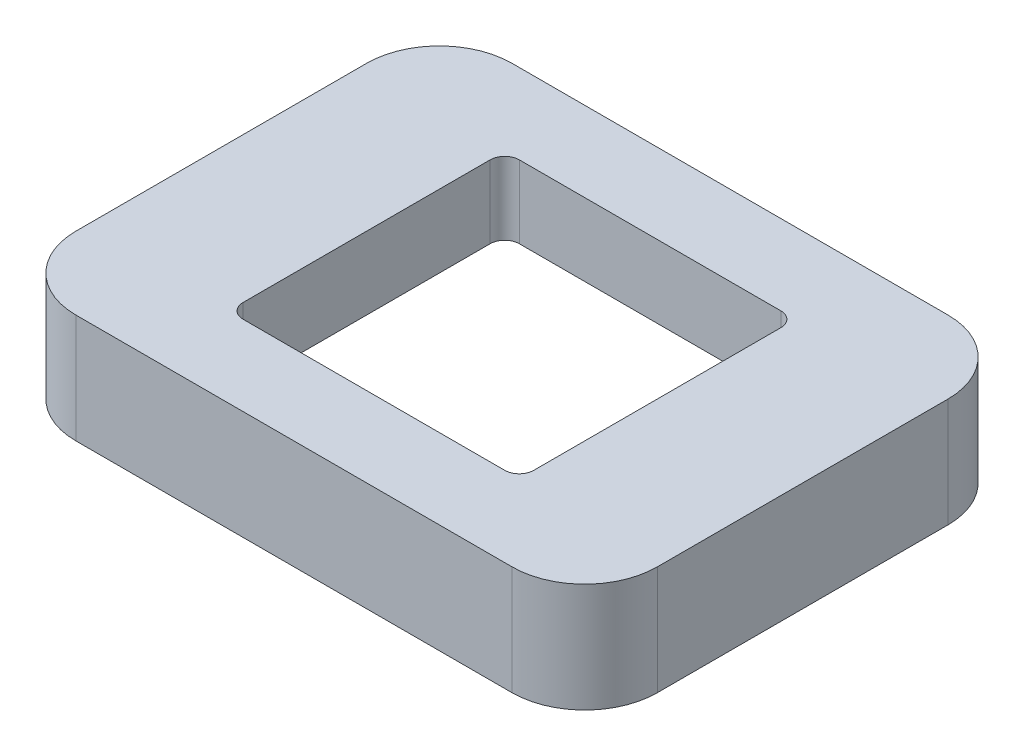
SolidWorks part; units mm, degrees
ref_plane "Plan de face" through (0, 0, 0) normal (0, 0, 1) x (1, 0, 0)
ref_plane "Plan de dessus" through (0, 0, 0) normal (0, 1, 0) x (1, 0, 0)
ref_plane "Plan de droite" through (0, 0, 0) normal (1, 0, 0) x (0, 0, -1)
sketch "Esquisse1" plane through (0, 0, 0) normal (0, 1, 0) x (1, 0, 0)
  line L1 (10, 0) -> (70, 0)
  line L2 (0, -10) -> (0, -50)
  line L3 (10, -60) -> (70, -60)
  line L4 (80, -10) -> (80, -50)
  line L13 (58, -49) -> (22, -49)
  line L14 (60, -47) -> (60, -13)
  line L15 (58, -11) -> (22, -11)
  line L16 (20, -47) -> (20, -13)
  line L17 (60, -49) -> (20, -11) construction
  line L18 (60, -11) -> (20, -49) construction
  arc A0 (0, -50) -> (10, -60) centre (10, -50) ccw
  arc A1 (80, -50) -> (70, -60) centre (70, -50) cw
  arc A2 (0, -10) -> (10, 0) centre (10, -10) cw
  arc A3 (70, 0) -> (80, -10) centre (70, -10) cw
  arc A12 (60, -13) -> (58, -11) centre (58, -13) ccw
  arc A13 (22, -11) -> (20, -13) centre (22, -13) ccw
  arc A14 (20, -47) -> (22, -49) centre (22, -47) ccw
  arc A15 (60, -47) -> (58, -49) centre (58, -47) cw
  point P9 (80, -60)
  point P12 (0, 0)
  point P15 (80, 0)
  point P16 (40, -30)
  dimension "D3" = 10
  dimension "D4" = 40
  dimension "D6" = 38
  dimension "D7" = 30
  dimension "D8" = 2
  dimension "D1" = 80
  dimension "D2" = 60
  dimension "D5" = 40
extrude "Boss.-Extru.1" add sketch "Esquisse1" along normal blind 15
sketch "Esquisse2" plane through (0, 0, 0) normal (0, -1, 0) x (1, 0, 0)
  line L0 (70, 0) -> (10, 0) construction
  line L1 (8, 57) -> (72, 57)
  line L2 (3, 52) -> (3, 8)
  line L3 (8, 3) -> (72, 3)
  line L4 (77, 52) -> (77, 8)
  line L5 (10, 60) -> (70, 60) construction
  line L6 (80, 50) -> (80, 10) construction
  line L7 (0, 10) -> (0, 50) construction
  arc A0 (3, 52) -> (8, 57) centre (8, 52) cw
  arc A1 (3, 8) -> (8, 3) centre (8, 8) ccw
  arc A2 (72, 3) -> (77, 8) centre (72, 8) ccw
  arc A3 (77, 52) -> (72, 57) centre (72, 52) ccw
  dimension "D5" = 5
  dimension "D1" = 3
  dimension "D2" = 3
  dimension "D3" = 3
  dimension "D4" = 3
extrude "Enlèv. mat.-Extru.1" cut sketch "Esquisse2" against normal blind 5
sketch "Esquisse3" plane through (0, 5, 0) normal (0, -1, 0) x (1, 0, 0)
  line L0 (65, 13.5) -> (65, 46.5) construction
  line L1 (65, 13.5) -> (15, 13.5) construction
  line L2 (15, 13.5) -> (15, 46.5) construction
  line L3 (15, 46.5) -> (65, 46.5) construction
  line L6 (72, 57) -> (8, 57) construction
  line L7 (3, 52) -> (3, 8) construction
  circle A0 centre (65, 13.5) radius 2.8
  circle A2 centre (65, 46.5) radius 2.8
  circle A3 centre (15, 13.5) radius 2.8
  circle A4 centre (15, 46.5) radius 2.8
  dimension "D1" = 5.6
  dimension "D2" = 10.5
  dimension "D3" = 50
  dimension "D4" = 33
  dimension "D5" = 12
extrude "Enlèv. mat.-Extru.2" cut sketch "Esquisse3" against normal blind 8.1
